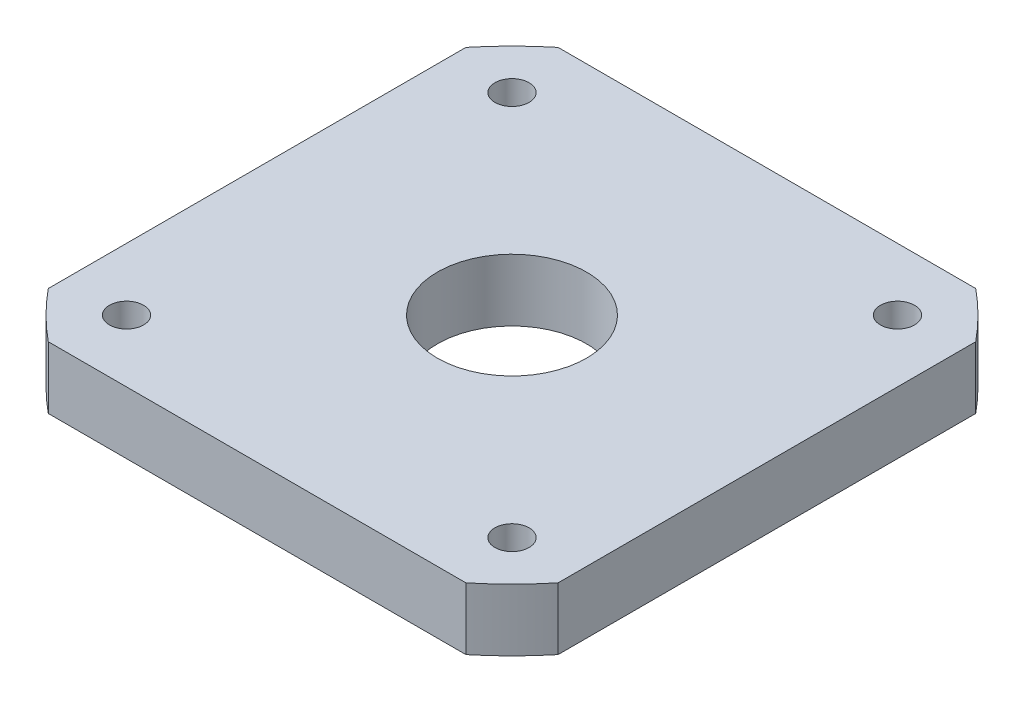
SolidWorks part; units mm, degrees
ref_plane "Front Plane" through (0, 0, 0) normal (0, 0, 1) x (1, 0, 0)
ref_plane "Top Plane" through (0, 0, 0) normal (0, 1, 0) x (1, 0, 0)
ref_plane "Right Plane" through (0, 0, 0) normal (1, 0, 0) x (0, 0, -1)
sketch "Sketch1" plane through (0, -13.7397, 0) normal (0, 1, 0) x (1, 0, 0)
  line L4 (16.2929, 20.5) -> (-17.2929, 20.5)
  line L5 (-21, 16.7929) -> (-21, -16.7929)
  line L6 (-17.2929, -20.5) -> (16.2929, -20.5)
  line L7 (20, -16.7929) -> (20, 16.7929)
  line L8 (16.2929, 20.5) -> (-17.2929, 20.5)
  line L9 (-21, 16.7929) -> (-21, -16.7929)
  line L10 (-17.2929, -20.5) -> (16.2929, -20.5)
  line L11 (20, -16.7929) -> (20, 16.7929)
  circle A0 centre (-0.5, 0) radius 6
  circle A1 centre (-16, 15.5) radius 1.375
  circle A2 centre (15, 15.5) radius 1.375
  circle A3 centre (-16, -15.5) radius 1.375
  arc A4 (-17.2929, 20.5) -> (-21, 16.7929) centre (-0.5, 0) ccw
  arc A5 (-21, -16.7929) -> (-17.2929, -20.5) centre (-0.5, 0) ccw
  arc A6 (16.2929, -20.5) -> (20, -16.7929) centre (-0.5, 0) ccw
  arc A7 (20, 16.7929) -> (16.2929, 20.5) centre (-0.5, 0) ccw
  arc A8 (-17.2929, 20.5) -> (-21, 16.7929) centre (-0.5, 0) ccw
  arc A9 (-21, -16.7929) -> (-17.2929, -20.5) centre (-0.5, 0) ccw
  arc A10 (16.2929, -20.5) -> (20, -16.7929) centre (-0.5, 0) ccw
  arc A11 (20, 16.7929) -> (16.2929, 20.5) centre (-0.5, 0) ccw
  circle A12 centre (15, -15.5) radius 1.375
  dimension "D1" = 0
extrude "Boss-Extrude1" add sketch "Sketch1" along normal blind 5
